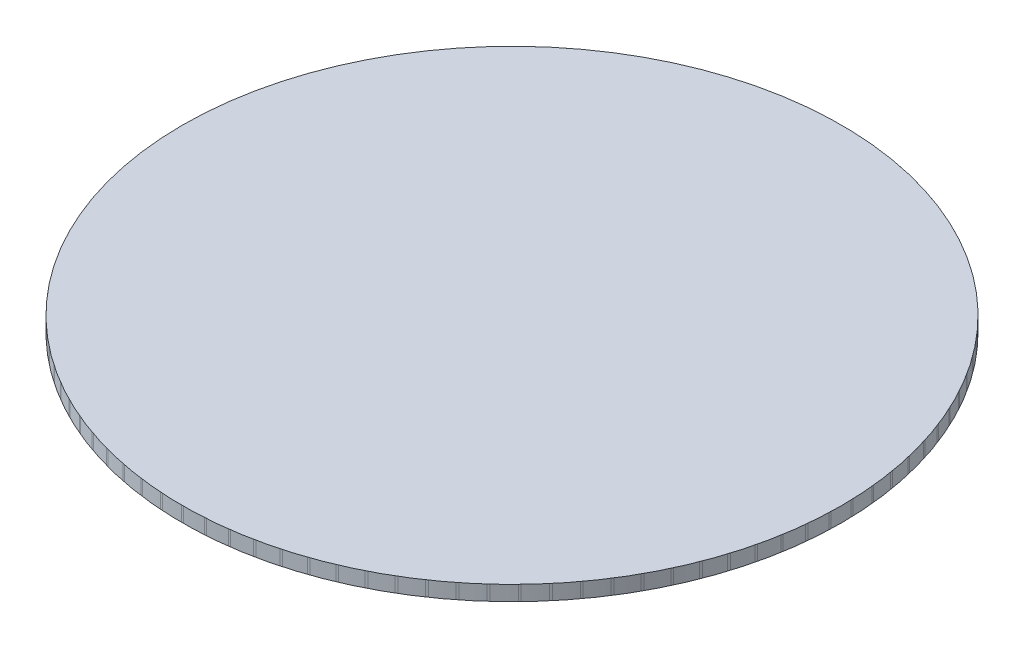
SolidWorks part; units mm, degrees
ref_plane "Front Plane" through (0, 0, 0) normal (0, 0, 1) x (1, 0, 0)
ref_plane "Top Plane" through (0, 0, 0) normal (0, 1, 0) x (1, 0, 0)
ref_plane "Right Plane" through (0, 0, 0) normal (1, 0, 0) x (0, 0, -1)
sketch "Sketch1" plane through (0, 0, 0) normal (0, 1, 0) x (1, 0, 0)
  circle A0 centre (0, 0) radius 4400
  circle A1 centre (0, 0) radius 2750
extrude "Boss-Extrude1" [suppressed] add sketch "Sketch1" against normal blind 2 contours A0 A1
sketch "Sketch2" [suppressed] plane through (0, 0, 0) normal (0, 1, 0) x (1, 0, 0)
  circle A0 centre (0, 0) radius 2750
extrude "Cut-Extrude1" [suppressed] cut sketch "Sketch2" against normal through all both and the other way through all
sketch "Sketch3" [suppressed] plane through (0, 0, 0) normal (0, 1, 0) x (1, 0, 0)
  circle A0 centre (0, 0) radius 4400
extrude "Extrude-Thin1" [suppressed] add sketch "Sketch3" along normal blind 200 separate body thin
sketch "Sketch4" plane through (0, 0, 0) normal (0, 1, 0) x (1, 0, 0)
  circle A0 centre (0, 0) radius 4400
extrude "Extrude-Thin2" add sketch "Sketch4" along normal blind 200 thin
